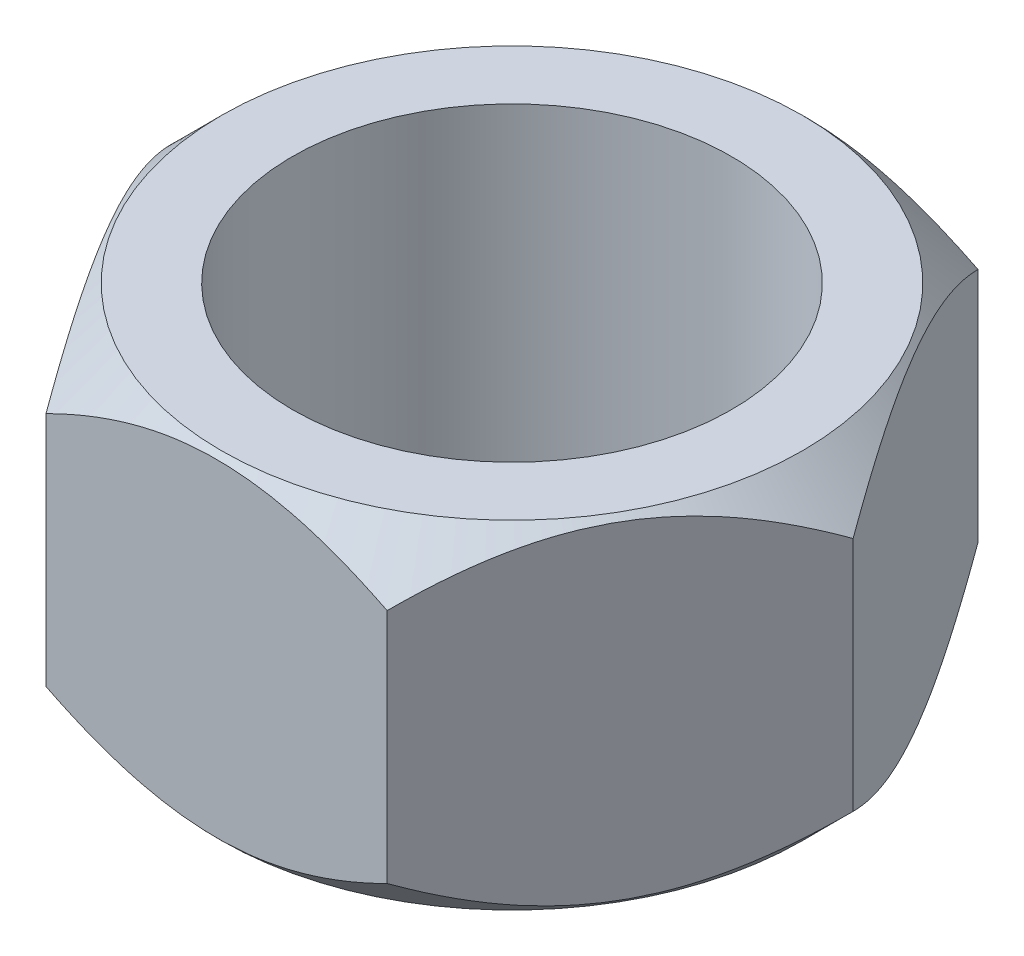
SolidWorks part; units mm, degrees
ref_plane "Front Plane" through (0, 0, 0) normal (0, 0, 1) x (1, 0, 0)
ref_plane "Top Plane" through (0, 0, 0) normal (0, 1, 0) x (1, 0, 0)
ref_plane "Right Plane" through (0, 0, 0) normal (1, 0, 0) x (0, 0, -1)
sketch "Sketch2" plane through (0, 0, 0) normal (0, 1, 0) x (1, 0, 0)
  line L1 (5.1326, 0) -> (2.5663, 4.445)
  line L2 (2.5663, 4.445) -> (-2.5663, 4.445)
  line L3 (-2.5663, 4.445) -> (-5.1326, 0)
  line L4 (-5.1326, 0) -> (-2.5663, -4.445)
  line L5 (-2.5663, -4.445) -> (2.5663, -4.445)
  line L6 (2.5663, -4.445) -> (5.1326, 0)
  circle A0 centre (0, 0) radius 4.445 construction
  point P1 (0, 0)
  dimension "D1" = 8.89
extrude "Boss-Extrude1" add sketch "Sketch2" along normal mid plane 5.08
sketch "Sketch3" plane through (0, 0, 0) normal (0, 0, 1) x (1, 0, 0)
  line L0 (4.3706, 2.54) -> (5.1326, 2.54)
  line L2 (5.1326, 2.54) -> (5.1326, 1.778)
  line L3 (5.1326, 1.778) -> (4.3706, 2.54)
  line L4 (0, 0) -> (0, 1.1822) construction
  dimension "D1" = 0.762
  dimension "D2" = 0.762
revolve "Cut-Revolve1" cut sketch "Sketch3" angle 360 about L4
hole_wizard "Hole1" positions "Sketch4" profile "Sketch5" legacy end condition through all
sketch "Sketch4" plane through (0, 2.54, 0) normal (0, 1, 0) x (1, 0, 0)
  point P0 (0, 0)
sketch "Sketch5" plane through (0, 2.54, 0) normal (1, 0, 0) x (0, 0, 1)
  line L0 (0, 0) -> (0, 5.08)
  line L1 (0, 5.08) -> (3.302, 5.08)
  line L2 (3.302, 5.08) -> (3.302, 0)
  line L3 (3.302, 0) -> (0, 0)
  line L4 (0, 110) -> (0, -10) construction
  dimension "Diameter" = 6.604
  dimension "Depth" = 5.08
mirror "Mirror1" about plane through (0, 0, 0) normal (0, 1, 0) of "Cut-Revolve1"
